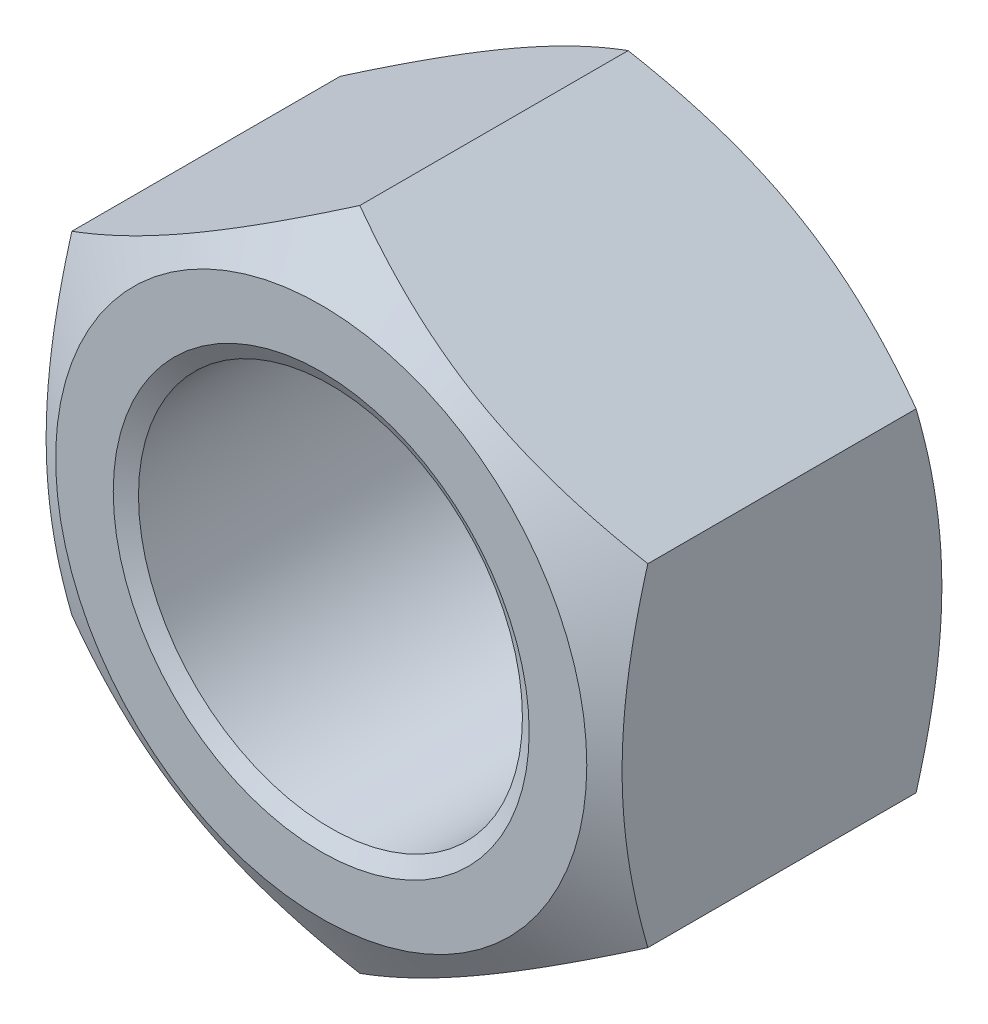
SolidWorks part; units mm, degrees
material "1023 탄소 강판(SS)"
ref_plane "Płaszczyzna przednia" through (0, 0, 0) normal (0, 0, 1) x (1, 0, 0)
ref_plane "Płaszczyzna górna" through (0, 0, 0) normal (0, 1, 0) x (1, 0, 0)
ref_plane "Płaszczyzna prawa" through (0, 0, 0) normal (1, 0, 0) x (0, 0, -1)
sketch "Szkic1" plane through (0, 0, 0) normal (0, 0, 1) x (1, 0, 0)
  line L1 (0, 10.3923) -> (-9, 5.1962)
  line L2 (-9, 5.1962) -> (-9, -5.1962)
  line L3 (-9, -5.1962) -> (0, -10.3923)
  line L4 (0, -10.3923) -> (9, -5.1962)
  line L5 (9, -5.1962) -> (9, 5.1962)
  line L6 (9, 5.1962) -> (0, 10.3923)
  circle A0 centre (0, 0) radius 9 construction
  circle A1 centre (0, 0) radius 6
  dimension "D1" = 12
  dimension "D2" = 18
extrude "Dodanie-wyciągnięcie1" add sketch "Szkic1" along normal blind 10.8
sketch "Szkic2" plane through (0, 0, 10.8) normal (0, 0, 1) x (1, 0, 0)
  circle A0 centre (0, 0) radius 8.3
extrude "Wytnij-wyciągnięcie1" cut sketch "Szkic2" against normal through all draft 60 flip side to cut
sketch "Szkic3" plane through (0, 0, 0) normal (0, 0, -1) x (-1, 0, 0)
  circle A0 centre (0, 0) radius 8.3
extrude "Wytnij-wyciągnięcie3" cut sketch "Szkic3" against normal through all draft 60 flip side to cut contours A0
chamfer "Sfazowanie2" distance 0.5 angle 30 2 edges at (6, 0, 10.8) (6, 0, 0)
